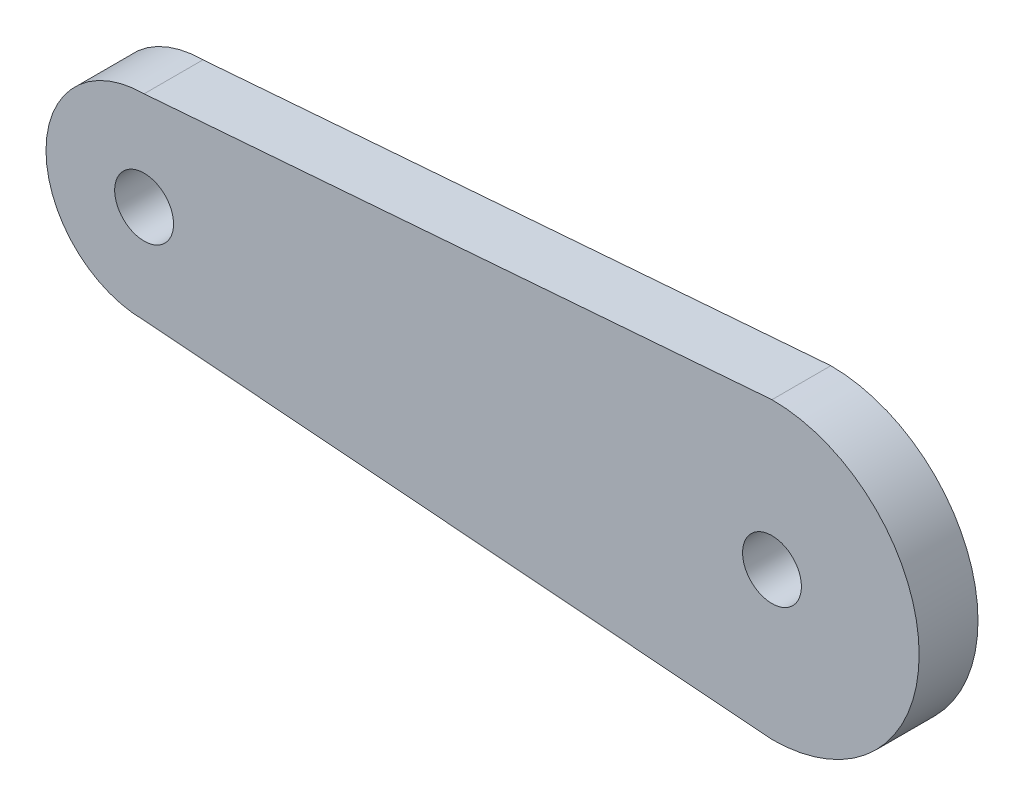
SolidWorks part; units mm, degrees
ref_plane "Front Plane" through (0, 0, 0) normal (0, 0, 1) x (1, 0, 0)
ref_plane "Top Plane" through (0, 0, 0) normal (0, 1, 0) x (1, 0, 0)
ref_plane "Right Plane" through (0, 0, 0) normal (1, 0, 0) x (0, 0, -1)
sketch "Sketch1" plane through (0, 0, 0) normal (0, 0, 1) x (1, 0, 0)
  line L0 (0, 0) -> (32, 0) construction
  line L1 (0, 5) -> (0, -5) construction
  line L2 (32, 7.5) -> (32, -7.5) construction
  line L3 (0, 5) -> (32, 7.5)
  line L4 (0, -5) -> (32, -7.5)
  circle A0 centre (0, 0) radius 1.5
  circle A1 centre (32, 0) radius 1.5
  arc A2 (0, 5) -> (0, -5) centre (0, 0) ccw
  arc A3 (32, 7.5) -> (32, -7.5) centre (32, 0) cw
  dimension "D5" = 5
  dimension "D6" = 3
  dimension "D7" = 3
  dimension "D1" = 32
  dimension "D2" = 10
  dimension "D3" = 15
  dimension "D4" = 7.5
extrude "Boss-Extrude1" add sketch "Sketch1" along normal blind 3 contours A3 L3 A2 L4 A1 A0
